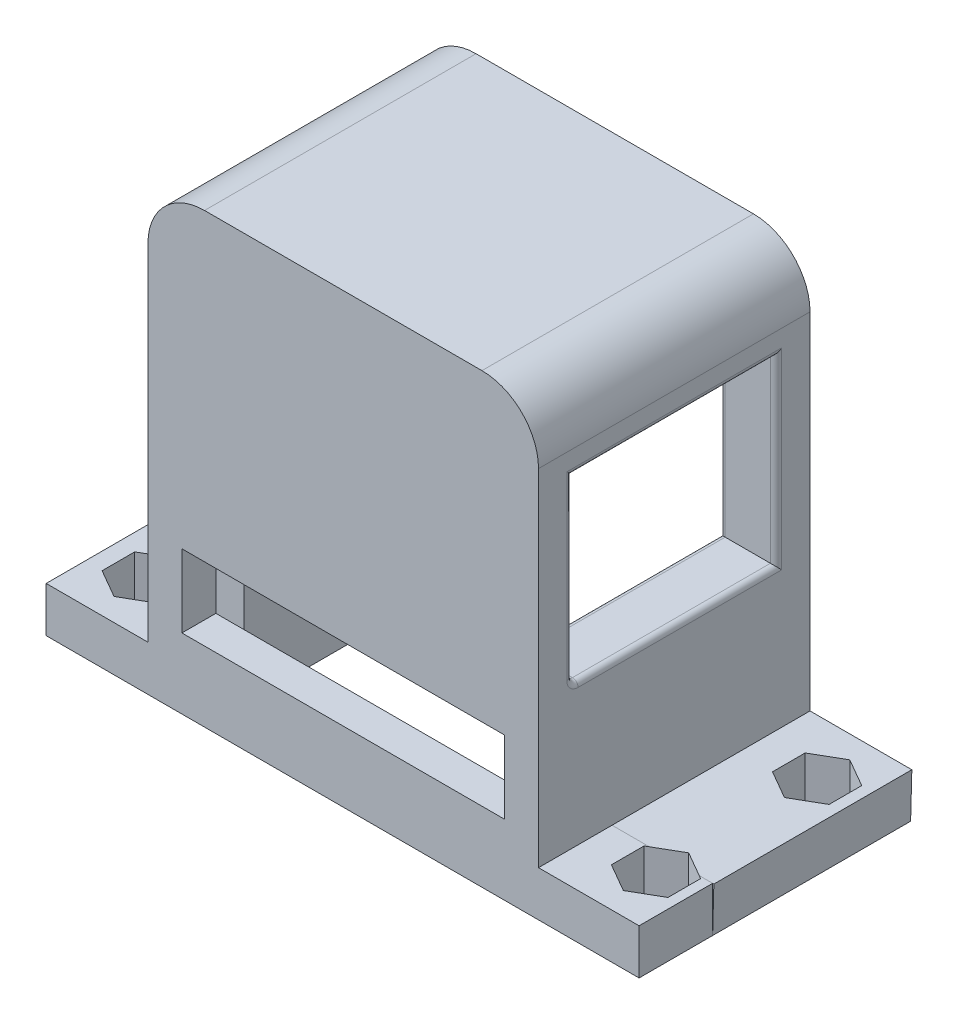
SolidWorks part; units mm, degrees
ref_plane "Front Plane" through (0, 0, 0) normal (0, 0, 1) x (1, 0, 0)
ref_plane "Top Plane" through (0, 0, 0) normal (0, 1, 0) x (1, 0, 0)
ref_plane "Right Plane" through (0, 0, 0) normal (1, 0, 0) x (0, 0, -1)
sketch "Sketch1" plane through (0, 0, 0) normal (0, 0, 1) x (1, 0, 0)
  line L0 (26.3162, 45.55) -> (26.3162, 41) construction
  line L1 (0.056, 6) -> (14.056, 6)
  line L2 (0.056, 6) -> (0.056, 10)
  line L3 (0.056, 10) -> (9.056, 10)
  line L6 (14.056, 6) -> (14.056, 41)
  line L8 (9.056, 10) -> (9.056, 39.5587)
  line L9 (14.3162, 45.55) -> (38.3162, 45.55)
  line L11 (14.056, 41) -> (38.5763, 41)
  line L14 (43.5763, 9.9985) -> (43.5763, 39.5587)
  line L15 (38.3162, 45.55) -> (41.4668, 45.55)
  line L16 (38.5763, 6) -> (38.5763, 41)
  line L18 (52.5763, 9.9985) -> (43.5763, 9.9985)
  line L19 (52.4668, 6) -> (52.5763, 9.9985)
  line L20 (52.4668, 6) -> (38.5763, 6)
  line L21 (9.056, 39.5587) -> (9.056, 45.55)
  line L22 (9.056, 45.55) -> (14.3162, 45.55)
  line L23 (41.4668, 45.55) -> (43.5763, 45.55)
  line L25 (43.5763, 45.55) -> (43.5763, 39.5587)
  point P1 (43.5763, 9.9985)
  dimension "D1" = 9
  dimension "D2" = 5
  dimension "D3" = 12
  dimension "D4" = 35
  dimension "D5" = 9
  dimension "D6" = 4.55
  dimension "D7" = 5
  dimension "D8" = 24.5203
  dimension "D9" = 35
  dimension "D10" = 4
  dimension "D11" = 4
extrude "Boss-Extrude1" add sketch "Sketch1" along normal blind 17.5
sketch "Sketch2" plane through (0, 0, 17.5) normal (0, 0, 1) x (1, 0, 0)
  line L0 (9.056, 10) -> (9.056, 45.55)
  line L1 (9.056, 45.55) -> (43.5763, 45.55)
  line L2 (43.5763, 45.55) -> (43.5763, 6)
  line L3 (38.5763, 6) -> (52.4668, 6) construction
  line L4 (43.5763, 6) -> (9.056, 6)
  line L5 (0.056, 6) -> (14.056, 6) construction
  line L6 (9.056, 6) -> (9.056, 10)
extrude "Boss-Extrude2" add sketch "Sketch2" along normal blind 6.5
sketch "Sketch4" plane through (0, 0, 17.5) normal (0, 0, -1) x (-1, 0, 0)
  line L1 (-38.5763, 41) -> (-14.056, 41)
  line L2 (-38.5763, 41) -> (-38.5763, 6)
  line L3 (-38.5763, 6) -> (-14.056, 6)
  line L4 (-14.056, 41) -> (-14.056, 6)
extrude "Cut-Extrude1" cut sketch "Sketch4" against normal blind 3.5
sketch "Sketch5" plane through (0, 0, 21) normal (0, 0, -1) x (-1, 0, 0)
  line L0 (-43.5763, 45.55) -> (-9.056, 45.55) construction
  line L1 (-38.5763, 41) -> (-14.9466, 41)
  line L2 (-38.5763, 41) -> (-38.5763, 43)
  line L3 (-38.5763, 43) -> (-14.9466, 43)
  line L4 (-14.9466, 41) -> (-14.9466, 43)
  dimension "D1" = 2.55
extrude "Cut-Extrude2" cut sketch "Sketch5" along normal blind 4.5
fillet "Fillet1" radius 5 2 edges at (9.056, 45.55, 12) (43.5763, 45.55, 12)
sketch "Sketch7" plane through (0, 0, 17.5) normal (0, 0, 1) x (1, 0, 0)
  line L1 (0.056, 10) -> (9.056, 10)
  line L2 (0.056, 10) -> (0.056, 6)
  line L3 (0.056, 6) -> (9.056, 6)
  line L4 (9.056, 10) -> (9.056, 6)
  line L5 (43.5763, 9.9985) -> (52.4668, 9.9985)
  line L6 (43.5763, 9.9985) -> (43.5763, 6)
  line L7 (43.5763, 6) -> (52.4668, 6)
  line L8 (52.4668, 9.9985) -> (52.4668, 6)
extrude "Boss-Extrude3" add sketch "Sketch7" along normal through all
sketch "Sketch6" plane through (0, 9.9986, 0) normal (0, 1, 0) x (1, 0, 0)
  line L0 (9.056, -24) -> (9.056, 0) construction
  line L8 (4.056, -22) -> (6.556, -20.5566)
  line L9 (6.556, -20.5566) -> (6.556, -17.6699)
  line L10 (6.556, -17.6699) -> (4.056, -16.2265)
  line L11 (52.4668, -24) -> (43.5763, -24) construction
  line L31 (4.056, -16.2265) -> (1.556, -17.6699)
  line L32 (1.556, -17.6699) -> (1.556, -20.5566)
  line L33 (43.5763, -24) -> (43.5763, -17.5) construction
  line L40 (52.5763, 0) -> (52.5763, -23.9863) construction
  line L45 (52.5763, -11.9931) -> (43.5763, -11.9931) construction
  line L46 (1.556, -20.5566) -> (4.056, -22)
  line L47 (43.5763, -17.5) -> (43.5763, 0) construction
  line L48 (0, 0) -> (0, -24.0071) construction
  line L49 (0, -12.0036) -> (8.9264, -12.0036) construction
  line L50 (1.556, -3.4505) -> (4.056, -2.0071)
  line L51 (1.556, -6.3373) -> (1.556, -3.4505)
  line L52 (4.056, -7.7806) -> (1.556, -6.3373)
  line L53 (6.556, -6.3373) -> (4.056, -7.7806)
  line L54 (6.556, -3.4505) -> (6.556, -6.3373)
  line L55 (4.056, -2.0071) -> (6.556, -3.4505)
  line L56 (9.056, -24) -> (0.056, -24) construction
  line L63 (46.5763, -3.4297) -> (49.0763, -1.9863)
  line L64 (46.5763, -6.3164) -> (46.5763, -3.4297)
  line L66 (49.0763, -22) -> (51.5763, -20.5566)
  line L67 (51.5763, -20.5566) -> (51.5763, -17.6699)
  line L68 (51.5763, -17.6699) -> (49.0763, -16.2265)
  line L69 (49.0763, -16.2265) -> (46.5763, -17.6699)
  line L70 (46.5763, -17.6699) -> (46.5763, -20.5566)
  line L71 (46.5763, -20.5566) -> (49.0763, -22)
  line L72 (49.0763, -7.7598) -> (46.5763, -6.3164)
  line L73 (51.5763, -6.3164) -> (49.0763, -7.7598)
  line L74 (51.5763, -3.4297) -> (51.5763, -6.3164)
  line L75 (49.0763, -1.9863) -> (51.5763, -3.4297)
  circle A1 centre (4.056, -19.1132) radius 2.5 construction
  circle A4 centre (49.0763, -19.1132) radius 2.5 construction
  dimension "D1" = 5
  dimension "D4" = 5
  dimension "D2" = 5
  dimension "D3" = 2
  dimension "D5" = 2
  dimension "D6" = 3
fillet "Fillet2" radius 1 2 edges at (38.5763, 23.5, 0) (14.056, 23.5, 0)
sketch "Sketch8" plane through (9.056, 0, 0) normal (-1, 0, 0) x (0, 0, 1)
  line L0 (24, 40.55) -> (24, 10) construction
  line L1 (3, 38.55) -> (21, 38.55)
  line L2 (3, 38.55) -> (3, 22.55)
  line L3 (3, 22.55) -> (21, 22.55)
  line L4 (21, 38.55) -> (21, 22.55)
  line L5 (24, 40.55) -> (0, 40.55) construction
  dimension "D1" = 18
  dimension "D2" = 16
  dimension "D3" = 3
  dimension "D4" = 2
extrude "Cut-Extrude4" cut sketch "Sketch8" against normal up to next
fillet "Fillet3" radius 0.5 8 edges at (11.556, 22.55, 21) (9.056, 22.55, 12) (9.056, 30.55, 3) (9.056, 30.55, 21) (9.056, 38.55, 12) (14.056, 22.55, 12) (14.056, 30.55, 3) (14.056, 14.275, 21)
sketch "Sketch9" plane through (43.5763, 0, 0) normal (1, 0, 0) x (0, 0, -1)
  line L0 (-3, 38.55) -> (-3, 22.55) construction
  line L1 (-21, 38.55) -> (-3, 38.55)
  line L2 (-21, 38.55) -> (-21, 22.55)
  line L3 (-21, 22.55) -> (-3, 22.55)
  line L4 (-3, 38.55) -> (-3, 22.55)
  line L5 (-21, 38.55) -> (-3, 38.55) construction
  dimension "D1" = 18
  dimension "D2" = 16
extrude "Cut-Extrude5" cut sketch "Sketch9" against normal up to next
fillet "Fillet4" radius 0.5 8 edges at (38.5763, 38.55, 12) (38.5763, 30.55, 3) (38.5763, 22.55, 12) (41.0763, 22.55, 21) (43.5763, 30.55, 21) (43.5763, 22.55, 12) (43.5763, 30.55, 3) (43.5763, 38.55, 12)
sketch "Sketch10" plane through (0, 0, 24) normal (0, 0, 1) x (1, 0, 0)
  line L0 (9.056, 40.55) -> (9.056, 10) construction
  line L1 (12.056, 18.6526) -> (40.5763, 18.6526)
  line L2 (12.056, 18.6526) -> (12.056, 12.2073)
  line L3 (12.056, 12.2073) -> (40.5763, 12.2073)
  line L4 (40.5763, 18.6526) -> (40.5763, 12.2073)
  line L5 (43.5763, 9.9985) -> (43.5763, 40.55) construction
  dimension "D1" = 3
  dimension "D2" = 3
extrude "Cut-Extrude6" cut sketch "Sketch10" against normal blind 3
extrude "Cut-Extrude7" cut sketch "Sketch6" against normal through all and the other way blind 10
